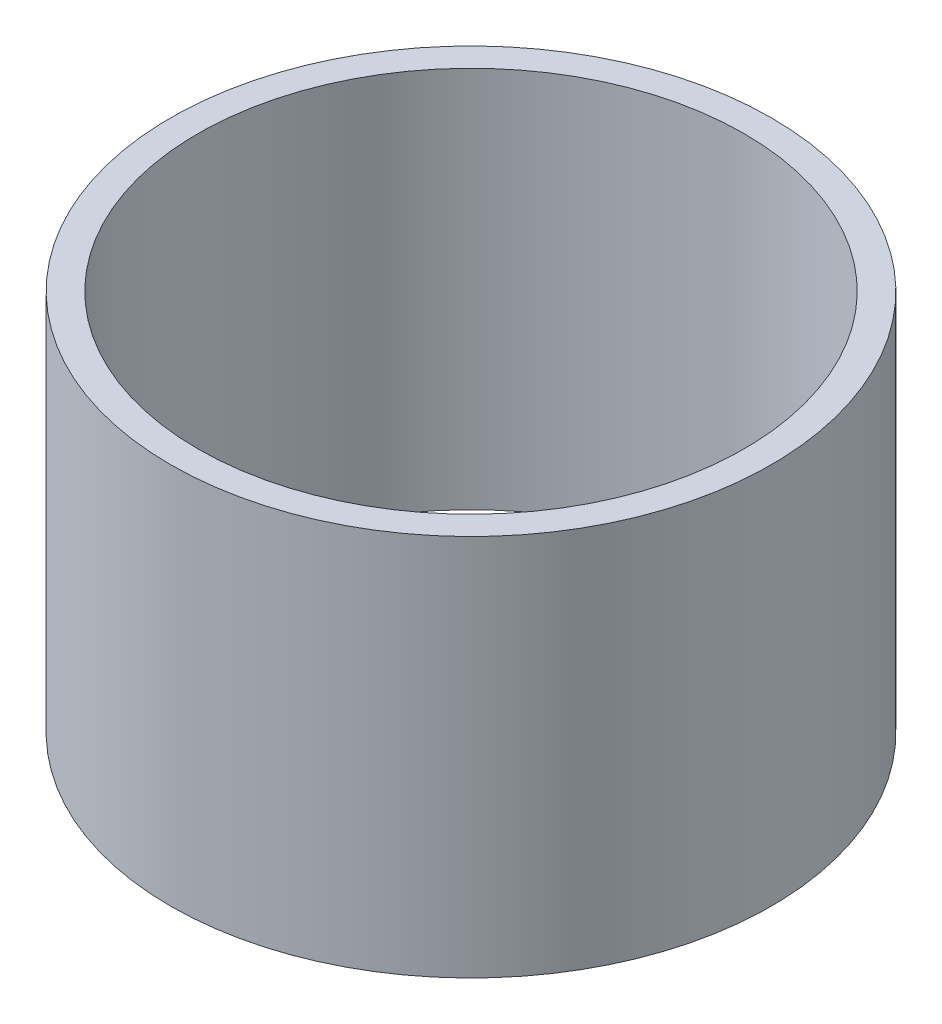
SolidWorks part; units mm, degrees
ref_plane "Front Plane" through (0, 0, 0) normal (0, 0, 1) x (1, 0, 0)
ref_plane "Top Plane" through (0, 0, 0) normal (0, 1, 0) x (1, 0, 0)
ref_plane "Right Plane" through (0, 0, 0) normal (1, 0, 0) x (0, 0, -1)
sketch "Sketch1" plane through (0, 0, 0) normal (0, 1, 0) x (1, 0, 0)
  circle A0 centre (0, 0) radius 63.5
  circle A1 centre (0, 0) radius 69.85
  dimension "D1" = 127
  dimension "D2" = 6.35
extrude "Boss-Extrude1" add sketch "Sketch1" along normal blind 88.9
